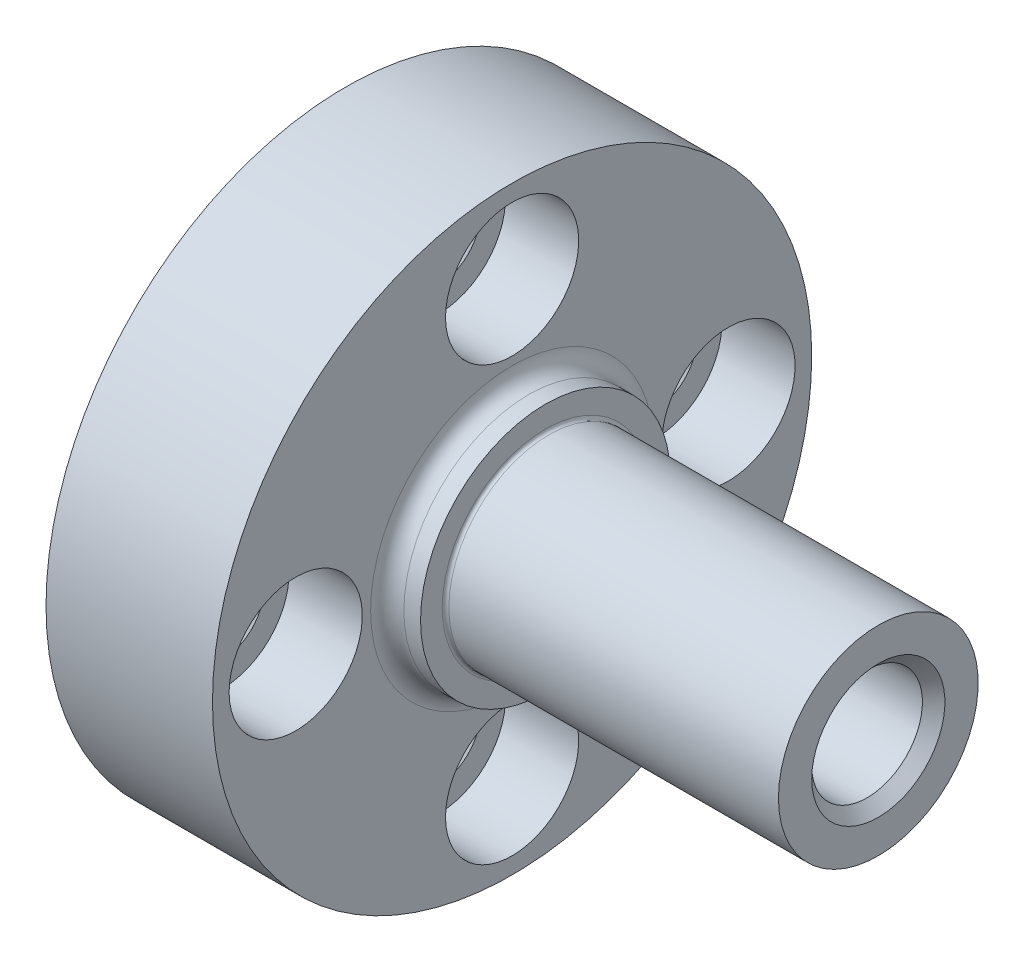
SolidWorks part; units mm, degrees
ref_plane "Front Plane" through (0, 0, 0) normal (0, 0, 1) x (1, 0, 0)
ref_plane "Top Plane" through (0, 0, 0) normal (0, 1, 0) x (1, 0, 0)
ref_plane "Right Plane" through (0, 0, 0) normal (1, 0, 0) x (0, 0, -1)
ref_plane "Plane1" through (0, 0, 0) normal (0, 0, 1) x (1, 0, 0)
sketch "Sketch1" plane through (0, 0, 0) normal (0, 0, 1) x (1, 0, 0)
  line L0 (0, 0) -> (0, 18)
  line L1 (0, 18) -> (10, 18)
  line L2 (10, 18) -> (10, 8.5)
  line L3 (11, 7.5) -> (12, 7.5)
  line L4 (12, 7.5) -> (12, 6.2)
  line L5 (12.2, 6) -> (32, 6)
  line L6 (32, 6) -> (32, 0)
  line L7 (32, 0) -> (0, 0)
  line L8 (32, 0) -> (0, 0) construction
  arc A0 (10, 8.5) -> (11, 7.5) centre (11, 8.5) ccw
  arc A1 (12, 6.2) -> (12.2, 6) centre (12.2, 6.2) ccw
revolve "Revolve1" add sketch "Sketch1" angle 360 about L8
ref_plane "Plane2" through (0, 0, 0) normal (0, 0, 1) x (1, 0, 0)
sketch "Sketch2" plane through (0, 0, 0) normal (0, 0, 1) x (1, 0, 0)
  line L0 (0, 13) -> (0, 15.5)
  line L1 (0, 15.5) -> (0.433, 15.067)
  line L2 (0.433, 15.067) -> (5.167, 15.067)
  line L3 (5.167, 15.067) -> (5.6, 15.5)
  line L4 (5.6, 15.5) -> (5.6, 17)
  line L5 (5.6, 17) -> (10, 17)
  line L6 (10, 17) -> (10, 13)
  line L7 (10, 13) -> (0, 13)
  line L8 (10, 13) -> (0, 13) construction
revolve "Cut-Revolve1" cut sketch "Sketch2" angle 360 about L8
ref_plane "Plane3" through (0, 0, 13) normal (0, 0, 1) x (1, 0, 0)
sketch "Sketch3" plane through (0, 0, 13) normal (0, 0, 1) x (1, 0, 0)
  line L0 (0, 0) -> (0, 2.5)
  line L1 (0, 2.5) -> (0.433, 2.067)
  line L2 (0.433, 2.067) -> (5.167, 2.067)
  line L3 (5.167, 2.067) -> (5.6, 2.5)
  line L4 (5.6, 2.5) -> (5.6, 4)
  line L5 (5.6, 4) -> (10, 4)
  line L6 (10, 4) -> (10, 0)
  line L7 (10, 0) -> (0, 0)
  line L8 (10, 0) -> (0, 0) construction
revolve "Cut-Revolve2" cut sketch "Sketch3" angle 360 about L8
ref_plane "Plane4" through (0, 0, 0) normal (0, 0, 1) x (1, 0, 0)
sketch "Sketch4" plane through (0, 0, 0) normal (0, 0, 1) x (1, 0, 0)
  line L0 (0, -13) -> (0, -10.5)
  line L1 (0, -10.5) -> (0.433, -10.933)
  line L2 (0.433, -10.933) -> (5.167, -10.933)
  line L3 (5.167, -10.933) -> (5.6, -10.5)
  line L4 (5.6, -10.5) -> (5.6, -9)
  line L5 (5.6, -9) -> (10, -9)
  line L6 (10, -9) -> (10, -13)
  line L7 (10, -13) -> (0, -13)
  line L8 (10, -13) -> (0, -13) construction
revolve "Cut-Revolve3" cut sketch "Sketch4" angle 360 about L8
ref_plane "Plane5" through (0, 0, -13) normal (0, 0, 1) x (1, 0, 0)
sketch "Sketch5" plane through (0, 0, -13) normal (0, 0, 1) x (1, 0, 0)
  line L0 (0, 0) -> (0, 2.5)
  line L1 (0, 2.5) -> (0.433, 2.067)
  line L2 (0.433, 2.067) -> (5.167, 2.067)
  line L3 (5.167, 2.067) -> (5.6, 2.5)
  line L4 (5.6, 2.5) -> (5.6, 4)
  line L5 (5.6, 4) -> (10, 4)
  line L6 (10, 4) -> (10, 0)
  line L7 (10, 0) -> (0, 0)
  line L8 (10, 0) -> (0, 0) construction
revolve "Cut-Revolve4" cut sketch "Sketch5" angle 360 about L8
ref_plane "Plane6" through (0, 0, 0) normal (0, 0, 1) x (1, 0, 0)
sketch "Sketch6" plane through (0, 0, 0) normal (0, 0, 1) x (1, 0, 0)
  line L0 (7, 0) -> (8.9188, 3.3235)
  line L1 (8.9188, 3.3235) -> (31.3235, 3.3235)
  line L2 (31.3235, 3.3235) -> (32, 4)
  line L3 (32, 4) -> (32, 0)
  line L4 (32, 0) -> (7, 0)
  line L5 (32, 0) -> (7, 0) construction
revolve "Cut-Revolve5" cut sketch "Sketch6" angle 360 about L5
